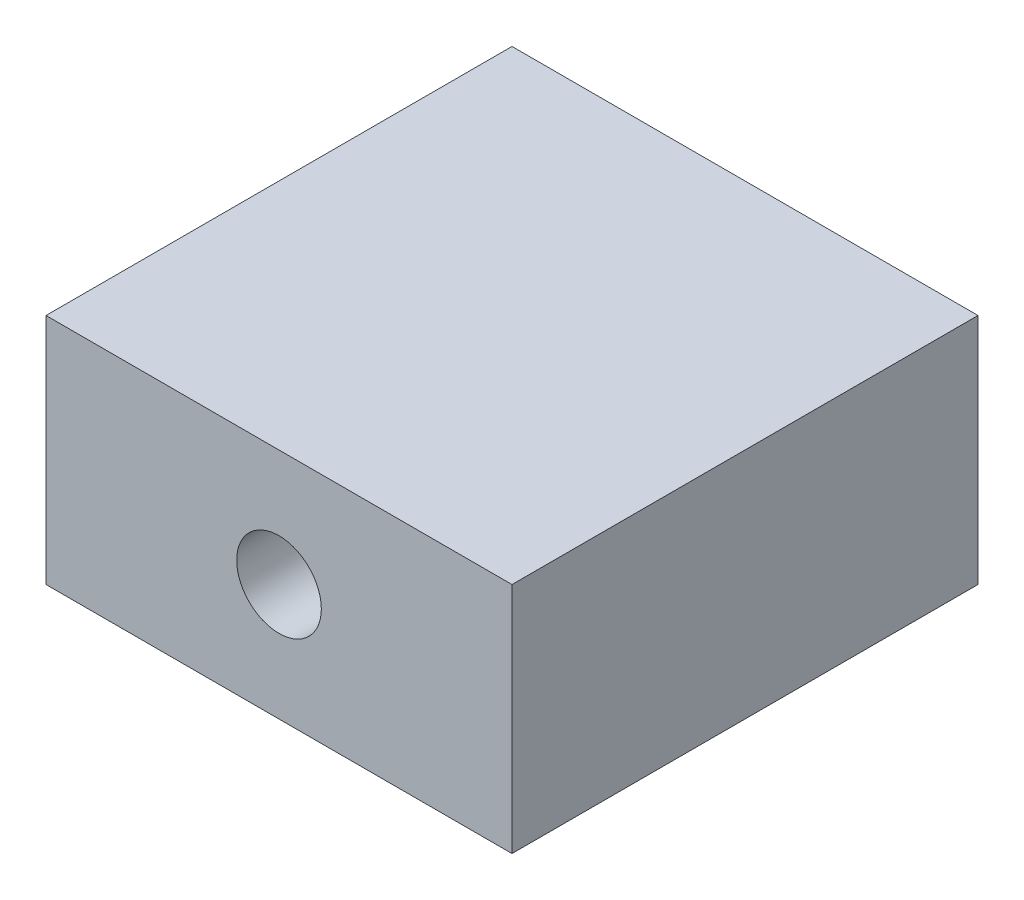
SolidWorks part; units mm, degrees
ref_plane "Front Plane" through (0, 0, 0) normal (0, 0, 1) x (1, 0, 0)
ref_plane "Top Plane" through (0, 0, 0) normal (0, 1, 0) x (1, 0, 0)
ref_plane "Right Plane" through (0, 0, 0) normal (1, 0, 0) x (0, 0, -1)
sketch "Sketch1" plane through (0, 0, 0) normal (0, 0, 1) x (1, 0, 0)
  line L1 (-76.2, -38.1) -> (76.2, -38.1)
  line L2 (-76.2, -38.1) -> (-76.2, 38.1)
  line L3 (-76.2, 38.1) -> (76.2, 38.1)
  line L4 (76.2, -38.1) -> (76.2, 38.1)
  line L5 (-76.2, -38.1) -> (76.2, 38.1) construction
  line L6 (-76.2, 38.1) -> (76.2, -38.1) construction
  point P0 (0, 0)
extrude "Boss-Extrude1" add sketch "Sketch1" along normal blind 152.4
sketch "Sketch2" plane through (0, 0, 0) normal (0, 0, 1) x (1, 0, 0)
  circle A0 centre (0, 0) radius 13.843
extrude "Cut-Extrude1" cut sketch "Sketch2" along normal through all
sketch "Sketch3" plane through (0, 0, 0) normal (0, 0, 1) x (1, 0, 0)
  circle A0 centre (0, 0) radius 5.1562
